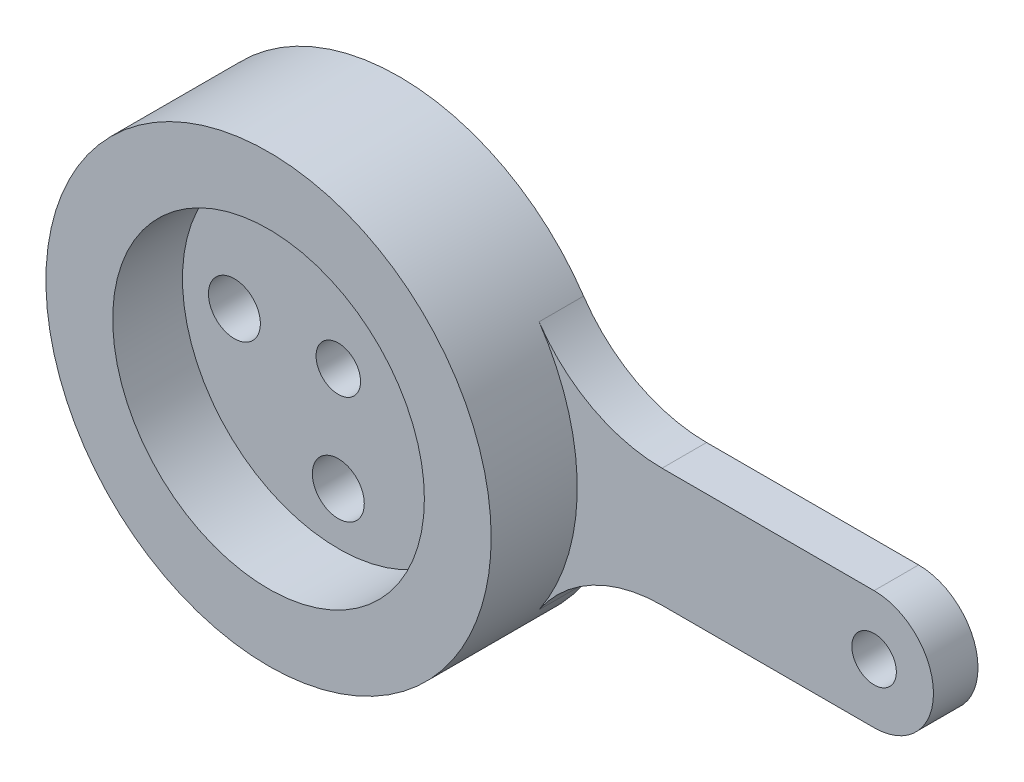
SolidWorks part; units mm, degrees
ref_plane "Front Plane" through (0, 0, 0) normal (0, 0, 1) x (1, 0, 0)
ref_plane "Top Plane" through (0, 0, 0) normal (0, 1, 0) x (1, 0, 0)
ref_plane "Right Plane" through (0, 0, 0) normal (1, 0, 0) x (0, 0, -1)
sketch "Sketch1" plane through (0, 0, 0) normal (0, 0, 1) x (1, 0, 0)
  circle A0 centre (0, 0) radius 15
  dimension "D1" = 30
extrude "Boss-Extrude1" add sketch "Sketch1" along normal blind 8.8
sketch "Sketch2" plane through (0, 0, 8.8) normal (0, 0, 1) x (1, 0, 0)
  line L0 (0, 24.4728) -> (0, -21.6994) construction
  line L1 (-2.4697, 16.8881) -> (-4.5, 3.9686)
  line L2 (2.4697, 16.8881) -> (4.5, 3.9686)
  line L3 (0, 0) -> (-6, 0) construction
  line L4 (2.4697, -16.8881) -> (4.5, -3.9686)
  line L5 (-2.4697, -16.8881) -> (-4.5, -3.9686)
  arc A0 (-4.5, 3.9686) -> (-4.5, -3.9686) centre (0, 0) ccw
  arc A1 (2.4697, 16.8881) -> (-2.4697, 16.8881) centre (0, 16.5) ccw
  arc A2 (2.4697, -16.8881) -> (-2.4697, -16.8881) centre (0, -16.5) cw
  arc A3 (4.5, -3.9686) -> (4.5, 3.9686) centre (0, 0) ccw
  dimension "D1" = 12
  dimension "D2" = 5
  dimension "D3" = 16.5
  dimension "D4" = 4.5
extrude "Cut-Extrude1" cut sketch "Sketch2" against normal blind 5
sketch "Sketch3" plane through (0, 0, 3.8) normal (0, 0, 1) x (1, 0, 0)
  circle A0 centre (0, 0) radius 1.5
  dimension "D1" = 3
extrude "Cut-Extrude2" cut sketch "Sketch3" against normal blind 5
sketch "Sketch4" plane through (0, 0, 0) normal (0, 0, -1) x (-1, 0, 0)
  line L0 (-35, 0) -> (21.1999, 0) construction
  line L1 (-35, 4) -> (-14.4568, 4)
  line L2 (-35, -4) -> (-14.4568, -4)
  arc A0 (-35, 4) -> (-35, -4) centre (-35, 0) ccw
  circle A2 centre (0, 0) radius 15 construction
  arc A3 (-14.4568, 4) -> (-14.4568, -4) centre (0, 0) ccw
  dimension "D1" = 8
  dimension "D3" = 35
extrude "Boss-Extrude2" add sketch "Sketch4" against normal blind 3
fillet "Fillet1" radius 10 1 edges at (14.4568, 4, 1.5)
fillet "Fillet2" radius 10 1 edges at (14.4568, -4, 1.5)
sketch "Sketch6" plane through (0, 0, 3) normal (0, 0, 1) x (1, 0, 0)
  line L0 (20.7123, 4) -> (35, 4) construction
  circle A0 centre (35, 0) radius 1.5
  dimension "D1" = 4
  dimension "D2" = 35
  dimension "D3" = 3
extrude "Cut-Extrude4" cut sketch "Sketch6" against normal up to surface (3 mm away) up to face at (1.5, 0, 0)
sketch "Sketch7" plane through (0, 0, 3.8) normal (0, 0, 1) x (1, 0, 0)
  circle A0 centre (0, 0) radius 10.5
  dimension "D1" = 21
extrude "Cut-Extrude6" cut sketch "Sketch7" along normal up to surface (5 mm away) up to face at (-7.077, 0, 8.8)
sketch "Sketch8" plane through (0, 0, 3.8) normal (0, 0, 1) x (1, 0, 0)
  line L4 (-2.8081, 14.7348) -> (-3.572, 9.8737)
  line L5 (-3.572, -9.8737) -> (-2.8081, -14.7348)
  line L6 (2.8081, -14.7348) -> (3.572, -9.8737)
  line L7 (3.572, 9.8737) -> (2.8081, 14.7348)
  line L8 (-2.8081, 14.7348) -> (-3.572, 9.8737)
  line L9 (-3.572, -9.8737) -> (-2.8081, -14.7348)
  line L10 (2.8081, -14.7348) -> (3.572, -9.8737)
  line L11 (3.572, 9.8737) -> (2.8081, 14.7348)
  arc A4 (-3.572, 9.8737) -> (-3.572, -9.8737) centre (0, 0) ccw
  arc A5 (-2.8081, -14.7348) -> (2.8081, -14.7348) centre (0, 0) ccw
  arc A6 (3.572, -9.8737) -> (3.572, 9.8737) centre (0, 0) ccw
  arc A7 (2.8081, 14.7348) -> (-2.8081, 14.7348) centre (0, 0) ccw
  arc A8 (-3.572, 9.8737) -> (-3.572, -9.8737) centre (0, 0) ccw
  arc A9 (-2.8081, -14.7348) -> (2.8081, -14.7348) centre (0, 0) ccw
  arc A10 (3.572, -9.8737) -> (3.572, 9.8737) centre (0, 0) ccw
  arc A11 (2.8081, 14.7348) -> (-2.8081, 14.7348) centre (0, 0) ccw
  dimension "D1" = 0
extrude "Boss-Extrude3" add sketch "Sketch8" along normal blind 0.3
sketch "Sketch9" plane through (0, 0, 8.8) normal (0, 0, 1) x (1, 0, 0)
  line L0 (-2.8081, 14.7348) -> (-3.572, 9.8737) construction
  line L1 (-2.8081, 14.7348) -> (-3.572, 9.8737)
  line L2 (3.572, 9.8737) -> (2.8081, 14.7348) construction
  line L3 (3.572, 9.8737) -> (2.8081, 14.7348)
  line L4 (-3.572, -9.8737) -> (-2.8081, -14.7348) construction
  line L5 (-3.572, -9.8737) -> (-2.8081, -14.7348)
  line L6 (2.8081, -14.7348) -> (3.572, -9.8737) construction
  line L7 (2.8081, -14.7348) -> (3.572, -9.8737)
  arc A0 (2.8081, 14.7348) -> (-2.8081, 14.7348) centre (0, 0) ccw construction
  arc A1 (2.8081, 14.7348) -> (-2.8081, 14.7348) centre (0, 0) ccw
  arc A2 (-2.8081, -14.7348) -> (2.8081, -14.7348) centre (0, 0) ccw construction
  arc A3 (-2.8081, -14.7348) -> (2.8081, -14.7348) centre (0, 0) ccw
  arc A4 (-3.572, -9.8737) -> (3.572, -9.8737) centre (0, 0) ccw
  arc A5 (3.572, 9.8737) -> (-3.572, 9.8737) centre (0, 0) ccw
extrude "Boss-Extrude4" add sketch "Sketch9" against normal up to surface (4.7 mm away) up to face at (0, 0, 4.1)
sketch "Sketch11" plane through (0, 0, 3.8) normal (0, 0, -1) x (-1, 0, 0)
  circle A1 centre (0, 0) radius 1.5
  circle A2 centre (0, 0) radius 1.5
  dimension "D1" = 0
extrude "Cut-Extrude7" cut sketch "Sketch11" against normal through all
sketch "Sketch12" plane through (0, 0, 0) normal (0, 0, -1) x (-1, 0, 0)
  line L0 (0, 0) -> (-7, 0) construction
  line L1 (0, -10.5797) -> (0, 12.2109) construction
  circle A0 centre (0, -7) radius 1.75
  circle A2 centre (-7, 0) radius 1.75
  circle A3 centre (7, 0) radius 1.75
  circle A4 centre (0, 7) radius 1.75
  dimension "D1" = 7
  dimension "D2" = 7
  dimension "D3" = 3.5
  dimension "D4" = 3.5
extrude "Cut-Extrude8" cut sketch "Sketch12" against normal through all
